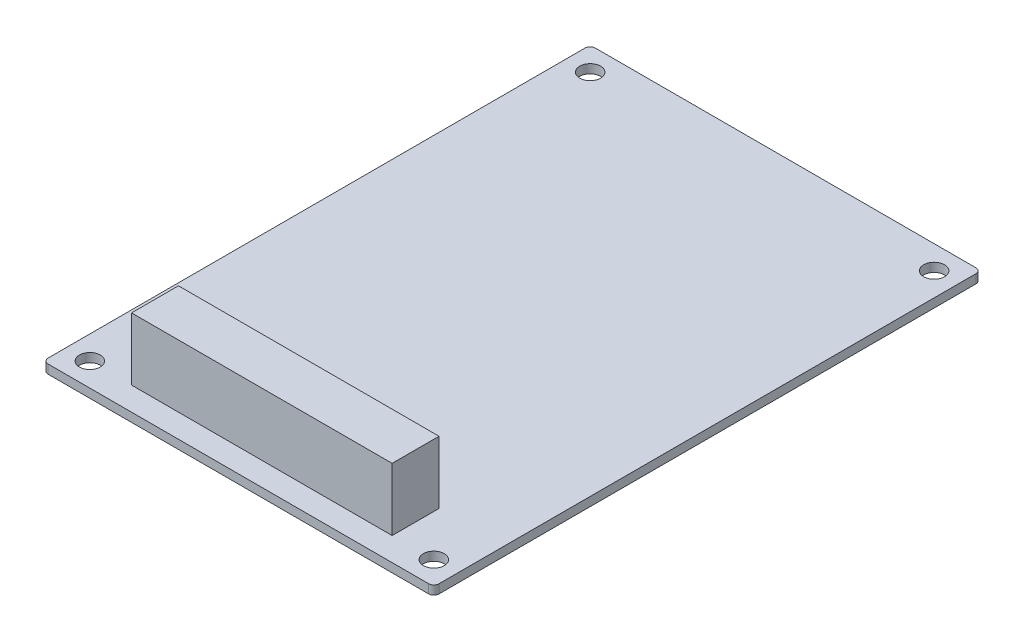
SolidWorks part; units mm, degrees
ref_plane "Plan de face" through (0, 0, 0) normal (0, 0, 1) x (1, 0, 0)
ref_plane "Plan de dessus" through (0, 0, 0) normal (0, 1, 0) x (1, 0, 0)
ref_plane "Plan de droite" through (0, 0, 0) normal (1, 0, 0) x (0, 0, -1)
sketch "Esquisse1" plane through (0, 0, 0) normal (0, 1, 0) x (1, 0, 0)
  line L1 (0, 0) -> (75, 0)
  line L2 (0, 0) -> (0, -105)
  line L3 (0, -105) -> (75, -105)
  line L4 (75, 0) -> (75, -105)
  dimension "D1" = 75
  dimension "D2" = 105
extrude "Boss.-Extru.1" add sketch "Esquisse1" along normal blind 1.7
hole_wizard "Diamètre du perçage Ø4.0 (4)1" positions "Esquisse2" profile "Esquisse3" hole size "Ø4.0" standard "Ansi Metric" end condition up to next
sketch "Esquisse2" plane through (0, 1.7, 0) normal (0, 1, 0) x (1, 0, 0)
  line L0 (0, 0) -> (0, -105) construction
  line L1 (0, -105) -> (75, -105) construction
  point P0 (70.5, -100.5)
  point P2 (4.5, -100.5)
  point P4 (70.5, -4.5)
  point P6 (4.5, -4.5)
  point P17 (4.5, -100.5)
  point P18 (0, 0)
  point P19 (0, 0)
  point P20 (0, 0)
  dimension "D1" = 66
  dimension "D2" = 4.5
  dimension "D3" = 4.5
  dimension "D4" = 96
  dimension "D5" = 66
sketch "Esquisse3" plane through (70.5, 1.7, 100.5) normal (1, 0, 0) x (0, 0, 1)
  line L0 (0, 0) -> (0, 1.7)
  line L1 (0, 1.7) -> (2, 1.7)
  line L2 (2, 1.7) -> (2, 0)
  line L5 (2, 0) -> (0, 0)
  line L11 (0, -6.35) -> (0, 107.95) construction
  dimension "Diamètre du perçage jusqu'au prochain" = 4
  dimension "Profondeur du perçage jusqu'au prochain" = 1.7
fillet "Congé1" radius 1 4 edges at (0, 0.85, 0) (75, 0.85, 0) (0, 0.85, 105) (75, 0.85, 105)
sketch "Esquisse4" plane through (0, 1.7, 0) normal (0, 1, 0) x (1, 0, 0)
  line L0 (75, -104) -> (75, -1) construction
  line L1 (12.5, -91.5) -> (62.5, -91.5)
  line L2 (12.5, -91.5) -> (12.5, -100.5)
  line L3 (12.5, -100.5) -> (62.5, -100.5)
  line L4 (62.5, -91.5) -> (62.5, -100.5)
  line L5 (1, -105) -> (74, -105) construction
  point P4 (37.5, -100.5)
  point P7 (62.5, -96)
  dimension "D1" = 37.5
  dimension "D2" = 9
  dimension "D3" = 9
  dimension "D4" = 50
extrude "Boss.-Extru.2" add sketch "Esquisse4" along normal blind 12 and the other way blind 5
